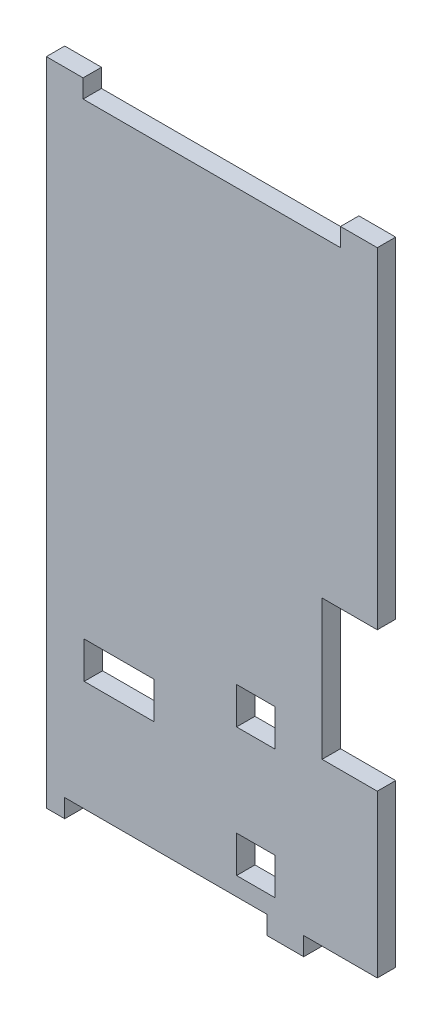
SolidWorks part; units mm, degrees
ref_plane "Plan de face" through (0, 0, 0) normal (0, 0, 1) x (1, 0, 0)
ref_plane "Plan de dessus" through (0, 0, 0) normal (0, 1, 0) x (1, 0, 0)
ref_plane "Plan de droite" through (0, 0, 0) normal (1, 0, 0) x (0, 0, -1)
sketch "Esquisse1" plane through (0, 0, 0) normal (0, 0, 1) x (1, 0, 0)
  line L0 (90, 82) -> (90, 167)
  line L1 (5, 0) -> (60, 0)
  line L2 (0, 0) -> (0, 167)
  line L3 (10, 167) -> (80, 167)
  line L4 (90, 0) -> (90, 44)
  line L5 (90, 82) -> (75, 82)
  line L6 (0, 167) -> (0, 172)
  line L7 (0, 172) -> (10, 172)
  line L8 (10, 167) -> (10, 172)
  line L9 (0, 0) -> (0, -5)
  line L10 (90, 167) -> (90, 172)
  line L11 (90, 172) -> (80, 172)
  line L12 (80, 167) -> (80, 172)
  line L13 (0, -5) -> (5, -5)
  line L14 (5, 0) -> (5, -5)
  line L16 (90, 44) -> (75, 44)
  line L17 (75, 82) -> (75, 44)
  line L18 (51.7344, 50) -> (62.2003, 50)
  line L19 (51.7344, 50) -> (51.7344, 40)
  line L20 (51.7344, 40) -> (62.2003, 40)
  line L25 (62.2003, 50) -> (62.2003, 40)
  line L32 (51.7344, 15) -> (62.2003, 15)
  line L34 (51.7344, 15) -> (51.7344, 5)
  line L35 (51.7344, 5) -> (62.2003, 5)
  line L37 (62.2003, 15) -> (62.2003, 5)
  line L54 (29.3073, 40) -> (10.2917, 40)
  line L55 (29.3073, 40) -> (29.3073, 30)
  line L56 (29.3073, 30) -> (10.2917, 30)
  line L57 (10.2917, 40) -> (10.2917, 30)
  line L58 (70, 0) -> (90, 0)
  line L60 (60, 0) -> (60, -5)
  line L61 (60, -5) -> (70, -5)
  line L62 (70, 0) -> (70, -5)
  dimension "D1" = 167
  dimension "D2" = 90
  dimension "D3" = 10
  dimension "D4" = 5
  dimension "D5" = 5
  dimension "D6" = 15
  dimension "D7" = 38
  dimension "D8" = 82
  dimension "D11" = 10
  dimension "D12" = 20
extrude "Boss.-Extru.1" add sketch "Esquisse1" along normal blind 5
